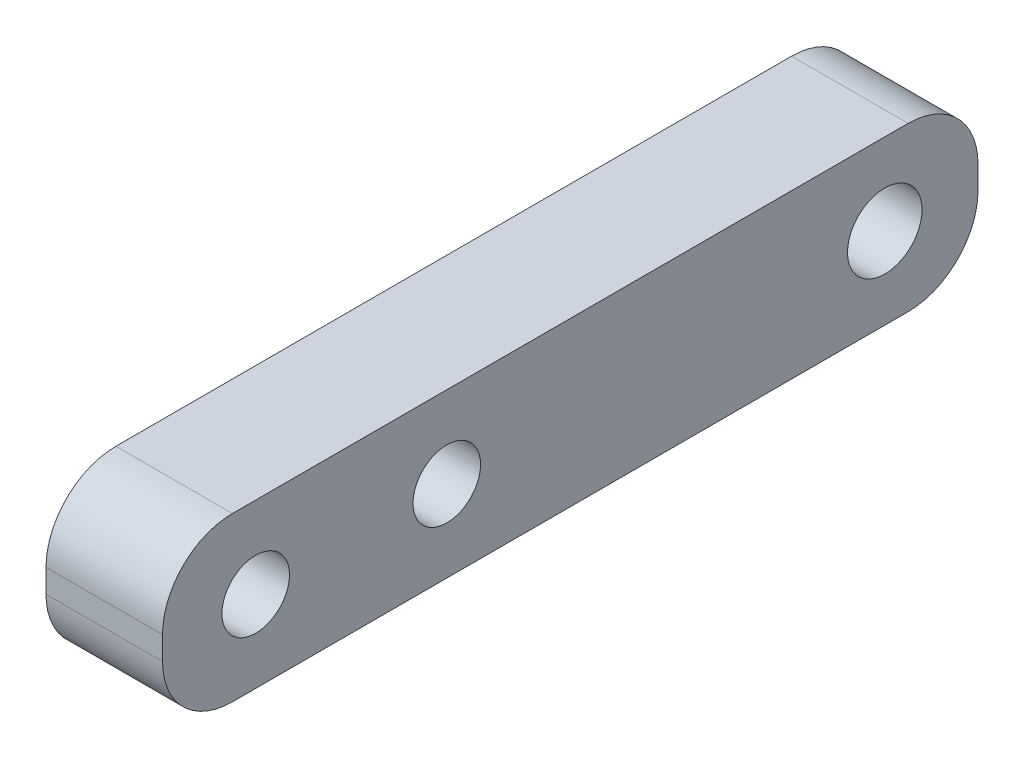
SolidWorks part; units mm, degrees
ref_plane "Front" through (0, 0, 0) normal (0, 0, 1) x (1, 0, 0)
ref_plane "Top" through (0, 0, 0) normal (0, 1, 0) x (1, 0, 0)
ref_plane "Right" through (0, 0, 0) normal (1, 0, 0) x (0, 0, -1)
sketch "Sketch1" plane through (0, 0, 0) normal (1, 0, 0) x (0, 0, -1)
  line L1 (0, 0) -> (35, 0)
  line L2 (0, 0) -> (0, -7)
  line L3 (0, -7) -> (35, -7)
  line L4 (35, 0) -> (35, -7)
  dimension "D1" = 7
  dimension "D2" = 35
extrude "Boss-Extrude1" add sketch "Sketch1" along normal blind 5
sketch "Sketch2" plane through (5, 0, 0) normal (1, 0, 0) x (0, 0, -1)
  line L0 (35, 0) -> (0, 0) construction
  line L1 (0, 0) -> (0, -7) construction
  line L2 (35, -7) -> (35, 0) construction
  circle A0 centre (4, -3.5) radius 1.45
  circle A1 centre (12.2, -3.5) radius 1.45
  circle A2 centre (31, -3.5) radius 1.6
  dimension "D1" = 2.9
  dimension "D2" = 2.9
  dimension "D3" = 3.2
  dimension "D4" = 3.5
  dimension "D5" = 3.5
  dimension "D6" = 3.5
  dimension "D7" = 4
  dimension "D8" = 4
  dimension "D9" = 22.8
extrude "Cut-Extrude1" cut sketch "Sketch2" against normal through all
fillet "Fillet1" radius 3 4 edges at (2.5, -7, -35) (2.5, 0, -35) (2.5, 0, 0) (2.5, -7, 0)
